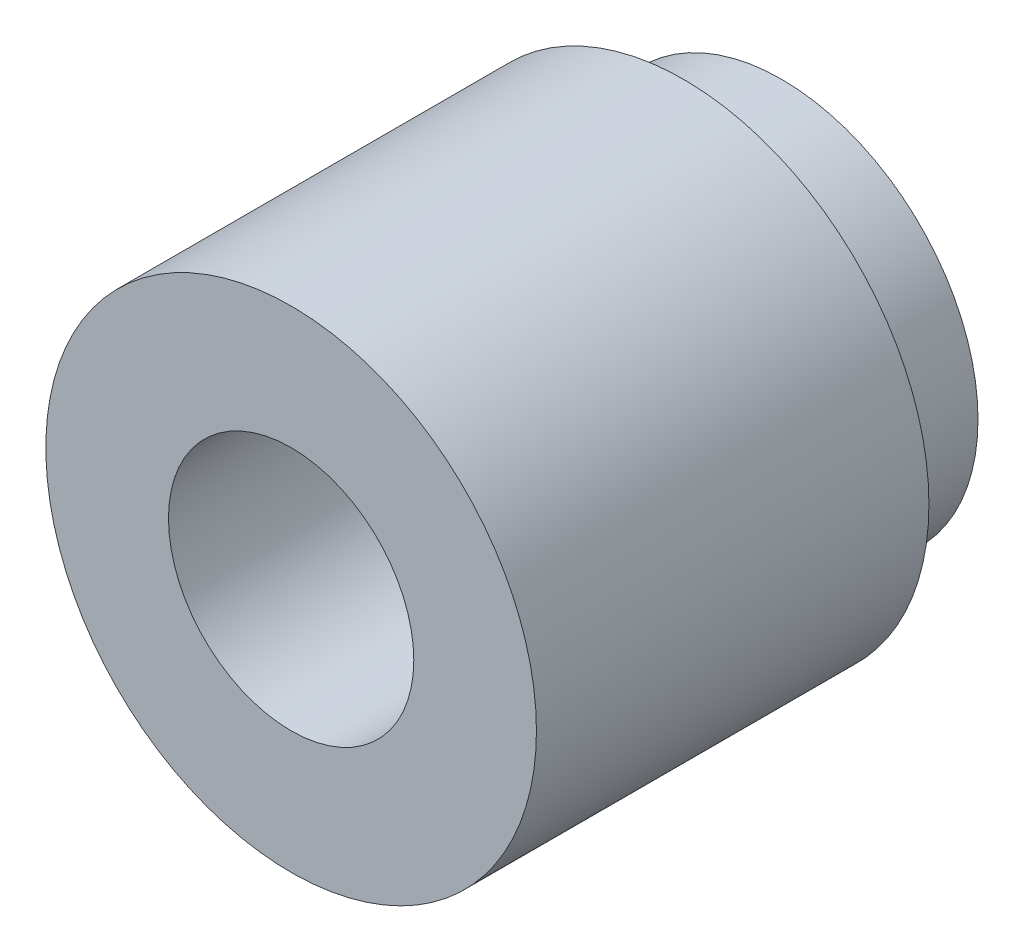
SolidWorks part; units mm, degrees
ref_plane "前视基准面" through (0, 0, 0) normal (0, 0, 1) x (1, 0, 0)
ref_plane "上视基准面" through (0, 0, 0) normal (0, 1, 0) x (1, 0, 0)
ref_plane "右视基准面" through (0, 0, 0) normal (1, 0, 0) x (0, 0, -1)
sketch "草图1" plane through (0, 0, 0) normal (0, 0, 1) x (1, 0, 0)
  circle A0 centre (0, 0) radius 1.25
  circle A1 centre (0, 0) radius 2.5
  dimension "内径" = 2.5
  dimension "外径" = 5
extrude "凸台-拉伸1" add sketch "草图1" along normal blind 4
sketch "草图2" plane through (0, 0, 0) normal (0, 0, -1) x (-1, 0, 0)
  circle A0 centre (0, 0) radius 1.25 construction
  circle A1 centre (0, 0) radius 1.25
  circle A2 centre (0, 0) radius 2
  dimension "外径" = 4
extrude "凸台-拉伸2" add sketch "草图2" along normal blind 1
